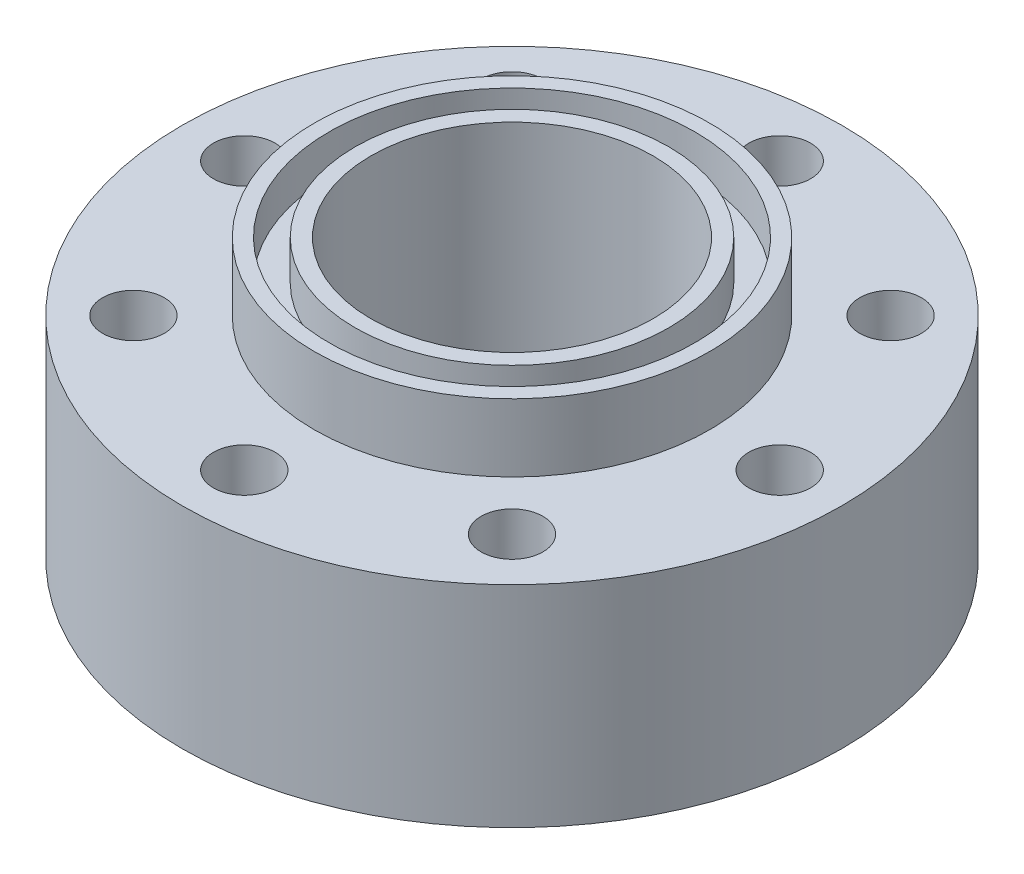
SolidWorks part; units mm, degrees
ref_plane "Ön Düzlem" through (0, 0, 0) normal (0, 0, 1) x (1, 0, 0)
ref_plane "Üst Düzlem" through (0, 0, 0) normal (0, 1, 0) x (1, 0, 0)
ref_plane "Sağ Düzlem" through (0, 0, 0) normal (1, 0, 0) x (0, 0, -1)
sketch "Çizim2" plane through (0, 0, 0) normal (0, 0, 1) x (1, 0, 0)
  line L0 (0, 65.5682) -> (0, -39.8864) construction
  line L1 (0, -39.8864) -> (125, -39.8864)
  line L4 (125, -39.8864) -> (125, 39.8864)
  line L5 (0, 65.5682) -> (0, -39.8864)
  line L9 (0, 65.5682) -> (75, 65.5682)
  line L10 (75, 39.8864) -> (75, 65.5682)
  line L14 (75, 39.8864) -> (125, 39.8864)
  point P0 (0, 0)
  point P6 (0, 39.8864)
  dimension "D4" = 50
revolve "Döndür1" add sketch "Çizim2" angle 360 about L0
sketch "Çizim3" plane through (0, 0, 0) normal (0, 0, 1) x (1, 0, 0)
  circle A0 centre (99.8958, 0) radius 9.3904
revolve "Kes-Döndür1" cut sketch "Çizim3" angle 360 about axis through (0, 65.5682, 0) along (0, 1, 0)
sketch "Çizim7" plane through (0, 0, 0) normal (0, 1, 0) x (1, 0, 0)
  circle A0 centre (0, 101.4937) radius 11.7181
  circle A1 centre (71.7669, 71.7669) radius 11.7181
  circle A2 centre (101.4937, 0) radius 11.7181
  circle A3 centre (71.7669, -71.7669) radius 11.7181
  circle A4 centre (0, -101.4937) radius 11.7181
  circle A5 centre (-71.7669, -71.7669) radius 11.7181
  circle A6 centre (-101.4937, 0) radius 11.7181
  circle A7 centre (-71.7669, 71.7669) radius 11.7181
  point P19 (0, 0)
  dimension "D1" = 8
extrude "Kes-Ekstrüzyon1" cut sketch "Çizim7" against normal through all both and the other way through all
sketch "Çizim8" plane through (0, 0, 0) normal (0, 1, 0) x (1, 0, 0)
  circle A0 centre (0, 0) radius 53.4994
extrude "Kes-Ekstrüzyon2" cut sketch "Çizim8" against normal through all both and the other way through all
sketch "Çizim9" plane through (0, 65.5682, 0) normal (0, 1, 0) x (1, 0, 0)
  circle A0 centre (0, 0) radius 69.3182
  circle A1 centre (0, 0) radius 59.4538
extrude "Kes-Ekstrüzyon3" cut sketch "Çizim9" against normal blind 15 and the other way through all contours A0 | A1
